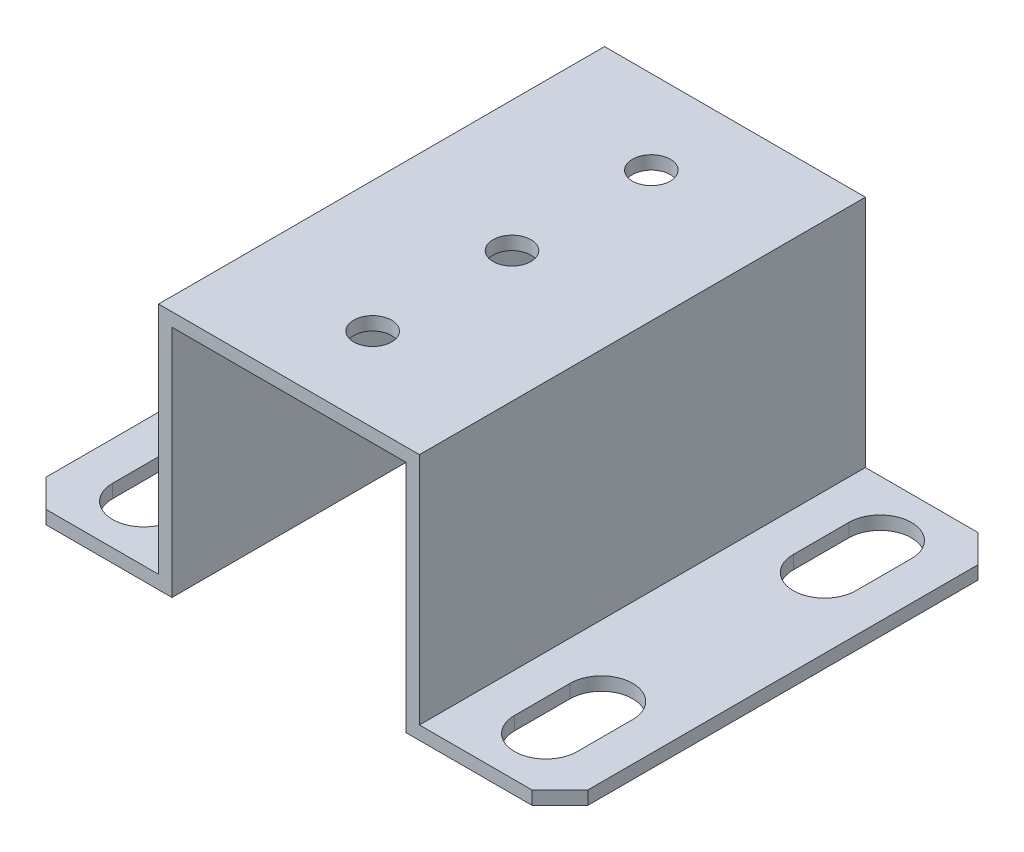
SolidWorks part; units mm, degrees
ref_plane "Front Plane" through (0, 0, 0) normal (0, 0, 1) x (1, 0, 0)
ref_plane "Top Plane" through (0, 0, 0) normal (0, 1, 0) x (1, 0, 0)
ref_plane "Right Plane" through (0, 0, 0) normal (1, 0, 0) x (0, 0, -1)
sketch "Sketch2" plane through (0, 0, 0) normal (0, 0, 1) x (1, 0, 0)
  line L9 (-14.859, 0) -> (-14.225, 0)
  line L13 (-14.225, 0) -> (14.859, 0)
  line L14 (14.859, 0) -> (14.859, -26.67)
  line L15 (14.859, -26.67) -> (30.861, -26.67)
  line L16 (30.861, -26.67) -> (30.861, -28.194)
  line L17 (30.861, -28.194) -> (13.335, -28.194)
  line L18 (13.335, -28.194) -> (13.335, -1.524)
  line L19 (13.335, -1.524) -> (-13.335, -1.524)
  line L20 (-13.335, -1.524) -> (-13.335, -28.194)
  line L21 (-13.335, -28.194) -> (-30.861, -28.194)
  line L22 (-30.861, -28.194) -> (-30.861, -26.67)
  line L23 (-30.861, -26.67) -> (-14.859, -26.67)
  line L24 (-14.859, -26.67) -> (-14.859, 0)
  line L25 (0, 12.716) -> (0, -28.0134) construction
  point P16 (-30.861, -27.432)
  point P17 (30.861, -27.432)
  point P18 (14.859, -13.335)
  dimension "D1" = 61.722
  dimension "D2" = 1.524
  dimension "D3" = 1.524
  dimension "D4" = 26.67
  dimension "D5" = 28.194
  dimension "D6" = 1.524
  dimension "D7" = 1.524
extrude "Boss-Extrude1" add sketch "Sketch2" along normal mid plane 50.8
sketch "Sketch3" plane through (0, 0, 0) normal (0, 1, 0) x (1, 0, 0)
  line L0 (14.859, 25.4) -> (-14.859, 25.4) construction
  line L4 (30.861, -25.4) -> (30.861, 25.4) construction
  line L6 (0, 0) -> (0, 25.4) construction
  line L7 (0, 0) -> (30.861, 0) construction
  circle A1 centre (0, -15.875) radius 2.159
  circle A2 centre (0, 15.875) radius 2.159
  circle A3 centre (0, 0) radius 2.159
  point P2 (-57.4221, 2.486)
  point P7 (0, 0)
  point P11 (0, 0)
  dimension "D1" = 4.318
  dimension "D2" = 9.525
  dimension "D4" = 41.275
extrude "Cut-Extrude3" cut sketch "Sketch3" against normal through all contours A2 | A3 | A1
sketch "Sketch9" plane through (0, -26.67, 0) normal (0, 1, 0) x (1, 0, 0)
  line L0 (22.8981, 19.0373) -> (22.8981, 12.7127) construction
  line L1 (26.4668, 19.0373) -> (26.4668, 12.7127)
  line L2 (19.3294, 19.0373) -> (19.3294, 12.7127)
  line L4 (30.861, 25.4) -> (14.859, 25.4) construction
  line L5 (30.861, -25.4) -> (30.861, 25.4) construction
  line L6 (0, 0) -> (0, 25.4) construction
  line L7 (14.859, 25.4) -> (-14.859, 25.4) construction
  line L8 (0, 0) -> (30.861, 0) construction
  line L9 (-22.8981, 19.0373) -> (-22.8981, 12.7127) construction
  line L10 (-26.4668, 19.0373) -> (-26.4668, 12.7127)
  line L11 (-19.3294, 19.0373) -> (-19.3294, 12.7127)
  line L12 (22.8981, -19.0373) -> (22.8981, -12.7127) construction
  line L13 (26.4668, -19.0373) -> (26.4668, -12.7127)
  line L14 (19.3294, -19.0373) -> (19.3294, -12.7127)
  line L15 (-22.8981, -19.0373) -> (-22.8981, -12.7127) construction
  line L16 (-26.4668, -19.0373) -> (-26.4668, -12.7127)
  line L17 (-19.3294, -19.0373) -> (-19.3294, -12.7127)
  arc A0 (26.4668, 19.0373) -> (19.3294, 19.0373) centre (22.8981, 19.0373) ccw
  arc A1 (19.3294, 12.7127) -> (26.4668, 12.7127) centre (22.8981, 12.7127) ccw
  arc A2 (-26.4668, 19.0373) -> (-19.3294, 19.0373) centre (-22.8981, 19.0373) cw
  arc A3 (-19.3294, 12.7127) -> (-26.4668, 12.7127) centre (-22.8981, 12.7127) cw
  arc A4 (26.4668, -19.0373) -> (19.3294, -19.0373) centre (22.8981, -19.0373) cw
  arc A5 (19.3294, -12.7127) -> (26.4668, -12.7127) centre (22.8981, -12.7127) cw
  arc A6 (-26.4668, -19.0373) -> (-19.3294, -19.0373) centre (-22.8981, -19.0373) ccw
  arc A7 (-19.3294, -12.7127) -> (-26.4668, -12.7127) centre (-22.8981, -12.7127) ccw
  point P2 (22.8981, 15.875)
  point P19 (-22.8981, 15.875)
  point P26 (22.8981, -15.875)
  point P33 (-22.8981, -15.875)
  dimension "D1" = 13.462
  dimension "D2" = 2.794
  dimension "D3" = 4.3942
  dimension "D4" = 7.1374
extrude "Cut-Extrude4" cut sketch "Sketch9" against normal through all
chamfer "Chamfer1" distance 3.175 angle 45 4 edges at (-30.861, -27.432, -25.4) (30.861, -27.432, -25.4) (30.861, -27.432, 25.4) (-30.861, -27.432, 25.4)
